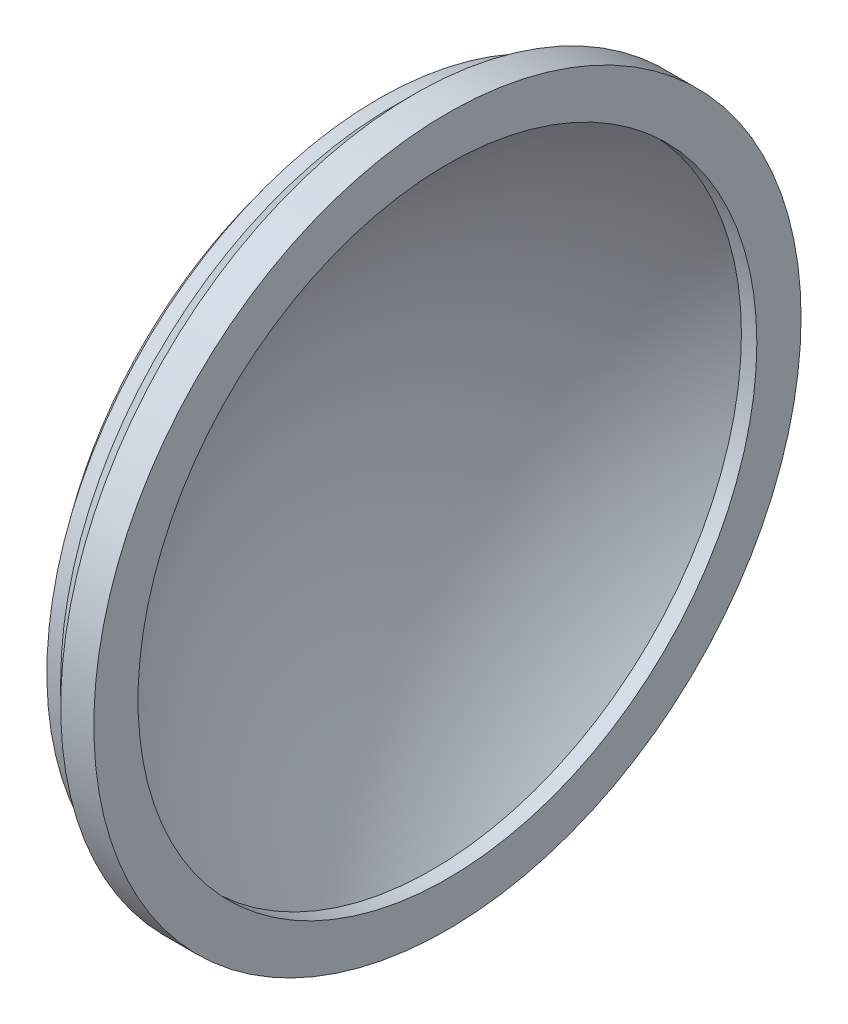
SolidWorks part; units mm, degrees
ref_plane "Front Plane" through (0, 0, 0) normal (0, 0, 1) x (1, 0, 0)
ref_plane "Top Plane" through (0, 0, 0) normal (0, 1, 0) x (1, 0, 0)
ref_plane "Right Plane" through (0, 0, 0) normal (1, 0, 0) x (0, 0, -1)
sketch "Sketch1" plane through (0, 0, 0) normal (0, 0, 1) x (1, 0, 0)
  line L0 (114.528, 0) -> (-135.0986, 0) construction
  line L1 (-18.7907, 56) -> (-16, 56)
  line L2 (-16, 56) -> (-16, 64)
  line L3 (-16, 64) -> (-22, 64)
  line L4 (-26, 60) -> (-22, 64)
  line L5 (-26, 60) -> (-28.5, 60)
  line L6 (-49.8454, 0) -> (-39.8454, 0)
  arc A0 (-18.7907, 56) -> (-39.8454, 0) centre (45.1546, 0) ccw
  arc A1 (-28.5, 60) -> (-49.8454, 0) centre (45.1546, 0) ccw
  dimension "D2" = 16
  dimension "D4" = 85
  dimension "D1" = 64
  dimension "D5" = 2.5
  dimension "D6" = 4
  dimension "D7" = 8
  dimension "D8" = 6
  dimension "D9" = 135
revolve "Revolve1" add sketch "Sketch1" angle 360 about L0
